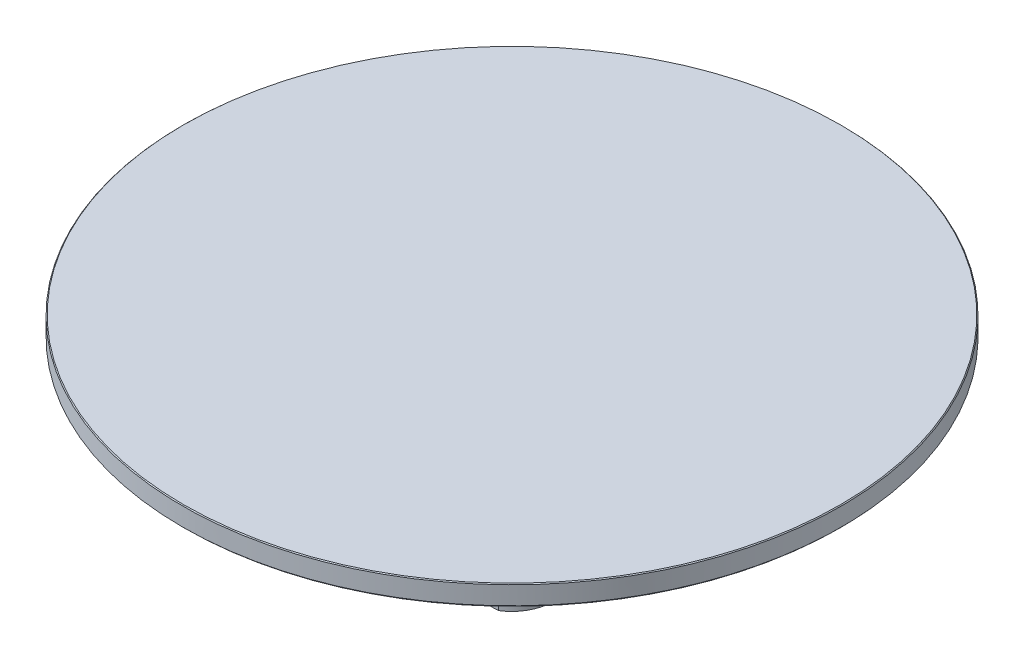
SolidWorks part; units mm, degrees
ref_plane "前视基准面" through (0, 0, 0) normal (0, 0, 1) x (1, 0, 0)
ref_plane "上视基准面" through (0, 0, 0) normal (0, 1, 0) x (1, 0, 0)
ref_plane "右视基准面" through (0, 0, 0) normal (1, 0, 0) x (0, 0, -1)
other "Configuration Table"
sketch "草图1" plane through (0, 0, 0) normal (0, 1, 0) x (1, 0, 0)
  circle A0 centre (0, 0) radius 79.5
  dimension "D1" = 159
extrude "凸台-拉伸1" add sketch "草图1" along normal blind 5
sketch "草图2" plane through (0, 0, 0) normal (0, -1, 0) x (-1, 0, 0)
  circle A0 centre (0, 0) radius 9.9
  dimension "D1" = 19.8
extrude "凸台-拉伸2" add sketch "草图2" along normal blind 50
chamfer "倒角1" distance 0.2 angle 45 1 edges at (0, 5, 79.5)
sketch "草图3" plane through (0, -50, 0) normal (0, -1, 0) x (-1, 0, 0)
  line L0 (4.8353, -8.7533) -> (-5.3657, -8.4386)
  arc A0 (-5.3657, -8.4386) -> (4.8353, -8.7533) centre (0, 0) ccw
  dimension "D1" = 20
  dimension "D2" = 8.6
extrude "切除-拉伸1" cut sketch "草图3" against normal up to surface (50 mm away) up to face at (0, 0, 9.9)
chamfer "倒角2" distance 0.4 angle 45 3 edges at (0, 0, 79.5) (0.2652, 0, 8.5959) (-0.3053, 0, -9.8953)
